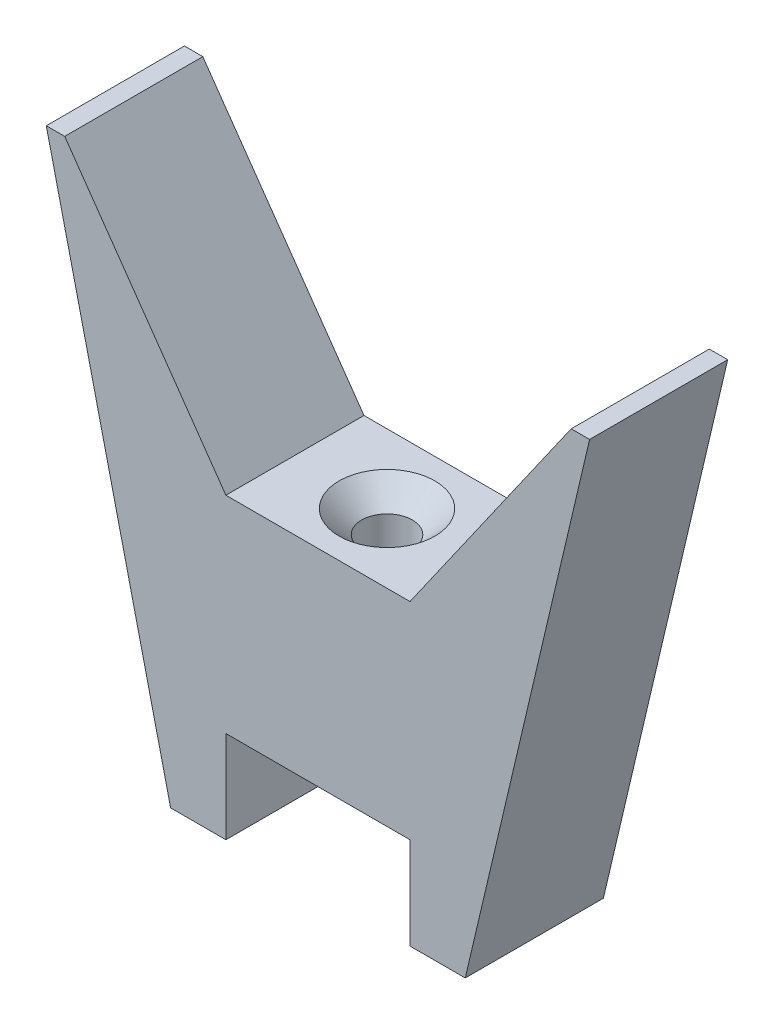
SolidWorks part; units mm, degrees
ref_plane "Спереди" through (0, 0, 0) normal (0, 0, 1) x (1, 0, 0)
ref_plane "Сверху" through (0, 0, 0) normal (0, 1, 0) x (1, 0, 0)
ref_plane "Справа" through (0, 0, 0) normal (1, 0, 0) x (0, 0, -1)
sketch "Эскиз1" plane through (0, 0, 0) normal (0, 0, 1) x (1, 0, 0)
  line L0 (-3910.7999, 0) -> (191629.1973, 0) construction
  line L1 (0, -3910.7999) -> (0, 191629.1973) construction
  line L2 (-10, 0) -> (-10, 10)
  line L3 (-10, 10) -> (10, 10)
  line L4 (-10, 0) -> (-16, 0)
  line L6 (-29.5052, 57.4104) -> (-27.5052, 57.4104)
  line L7 (-27.5052, 57.4104) -> (-10, 32.4104)
  line L9 (29.5052, 57.4104) -> (27.5052, 57.4104)
  line L10 (16, 0) -> (29.5052, 57.4104)
  line L11 (10, 0) -> (16, 0)
  line L12 (10, 0) -> (10, 10)
  line L13 (-10, 32.4104) -> (10, 32.4104)
  line L14 (27.5052, 57.4104) -> (10, 32.4104)
  line L15 (-29.5052, 57.4104) -> (-16, 0)
  line L16 (10, 10) -> (10, 0) construction
  line L17 (10, 10) -> (10, 0) construction
  circle A1 centre (0, 62.5868) radius 25.5 construction
  circle A2 centre (0, 62.5868) radius 25.5 construction
  point P15 (0, 32.4104)
  point P21 (0, 10)
  dimension "D3" = 10
  dimension "D4" = 20
  dimension "D6" = 70
  dimension "D7" = 25
  dimension "D8" = 6
  dimension "D9" = 2
extrude "Бобышка-Вытянуть1" add sketch "Эскиз1" along normal mid plane 15
hole_wizard "Зенковка для  винта с плоской головкой M51" positions "Трехмерный эскиз1" profile "Эскиз4" countersink size "M5" standard "Ansi Metric" end condition through all
sketch3d "Трехмерный эскиз1"
  line L0 (-10, 32.4104, 7.5) -> (10, 32.4104, -7.5)
  point P0 (0, 32.4104, 0)
sketch "Эскиз4" plane through (0, 32.4104, 0) normal (1, 0, 0) x (0, 0, 1)
  line L0 (0, 0) -> (0, 32.4104)
  line L1 (0, 32.4104) -> (2.75, 32.4104)
  line L2 (2.75, 32.4104) -> (2.75, 2.45)
  line L3 (2.75, 2.45) -> (5.2, 0)
  line L5 (5.2, 0) -> (0, 0)
  line L6 (-2.75, 2.45) -> (-5.2, 0) construction
  line L11 (0, -6.35) -> (0, 107.95) construction
  dimension "Диаметр сквозного отверстия" = 5.5
  dimension "Глубина сквозного отверстия" = 32.4104
  dimension "Диаметр передней зенковки" = 10.4
  dimension "Угол передней зенковки" = 90
